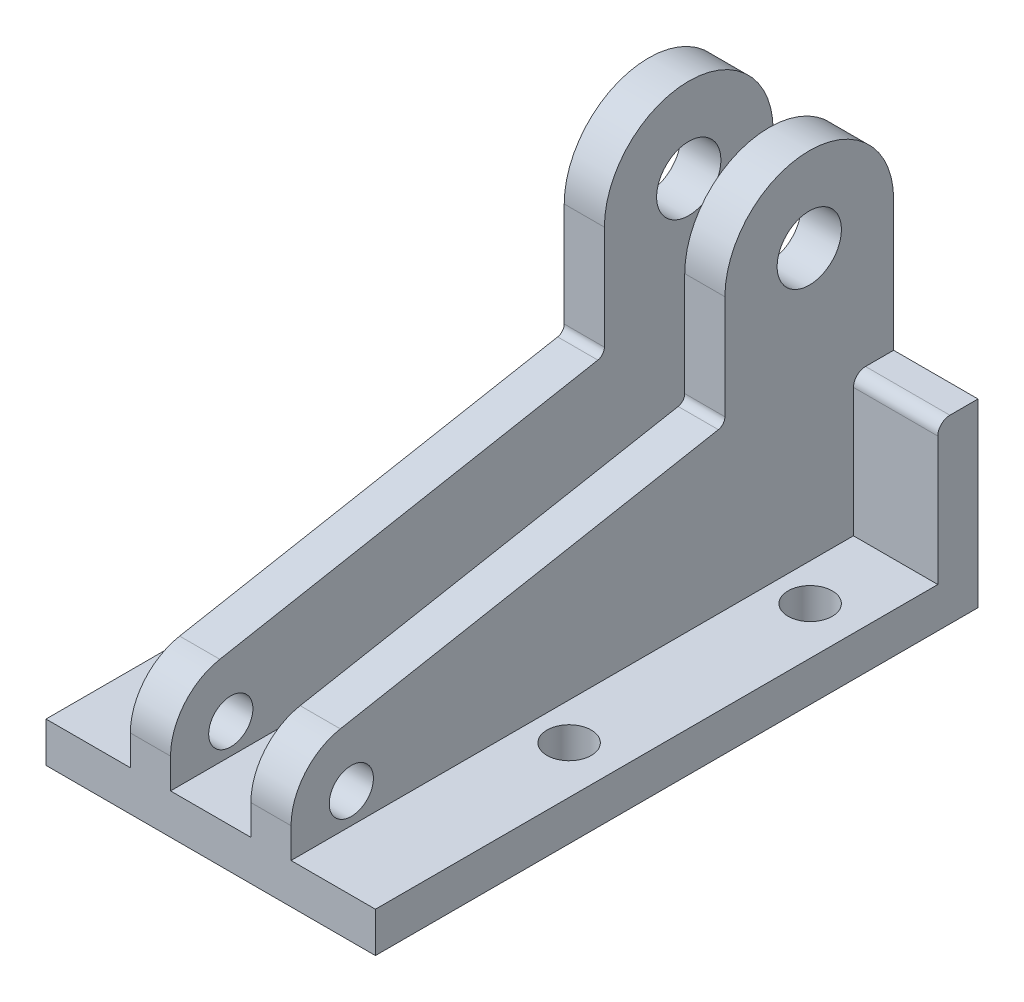
SolidWorks part; units mm, degrees
ref_plane "Front Plane" through (0, 0, 0) normal (0, 0, 1) x (1, 0, 0)
ref_plane "Top Plane" through (0, 0, 0) normal (0, 1, 0) x (1, 0, 0)
ref_plane "Right Plane" through (0, 0, 0) normal (1, 0, 0) x (0, 0, -1)
sketch "Sketch1" plane through (0, 0, 0) normal (1, 0, 0) x (0, 0, -1)
  line L0 (-84.2975, 0) -> (65.7025, 0)
  line L1 (65.7025, 0) -> (65.7025, 45)
  line L2 (-84.2975, 10) -> (55.7025, 10)
  line L3 (55.7025, 10) -> (55.7025, 42)
  line L4 (-84.2975, 0) -> (-84.2975, 10)
  line L5 (58.7025, 45) -> (65.7025, 45)
  line L6 (55.7025, 10) -> (55.7025, 45) construction
  arc A0 (58.7025, 45) -> (55.7025, 42) centre (58.7025, 42) ccw
  dimension "D4" = 3
  dimension "D1" = 150
  dimension "D2" = 45
  dimension "D3" = 10
extrude "Boss-Extrude1" add sketch "Sketch1" against normal blind 82
ref_plane "Plane1" through (-21, 0, 0) normal (1, 0, 0) x (0, 0, -1)
sketch "Sketch2" plane through (-21, 0, 0) normal (1, 0, 0) x (0, 0, -1)
  line L0 (65.7025, 45) -> (65.7025, 77.5314)
  line L1 (23.7025, 77.5314) -> (23.7025, 51.6632)
  line L2 (-84.2975, 10) -> (-84.2975, 17.5)
  line L3 (-72.0322, 32.2486) -> (22.0671, 49.6968)
  line L4 (55.7025, 10) -> (-84.2975, 10) construction
  line L5 (-84.2975, 10) -> (55.7025, 10)
  line L6 (55.7025, 10) -> (55.7025, 42)
  line L7 (65.7025, 45) -> (58.7025, 45)
  arc A0 (65.7025, 77.5314) -> (23.7025, 77.5314) centre (44.7025, 77.5314) ccw
  arc A1 (-72.0322, 32.2486) -> (-84.2975, 17.5) centre (-69.2975, 17.5) ccw
  arc A2 (55.7025, 42) -> (58.7025, 45) centre (58.7025, 42) cw
  circle A3 centre (44.7025, 77.5314) radius 8
  arc A4 (23.7025, 51.6632) -> (22.0671, 49.6968) centre (21.7025, 51.6632) cw
  circle A5 centre (-69.2975, 17.5) radius 5.5
  point P12 (-84.2975, 29.9743)
  point P25 (23.7025, 50)
  dimension "D1" = 21
  dimension "D3" = 15
  dimension "D5" = 2
  dimension "D2" = 7.5
  dimension "D4" = 40
extrude "Boss-Extrude2" add sketch "Sketch2" against normal blind 10
ref_plane "Plane2" through (-41, 0, 0) normal (1, 0, 0) x (0, 0, -1)
mirror "Mirror1" about plane through (-41, 0, 0) normal (1, 0, 0) of bodies 102
sketch "Sketch3" plane through (0, 10, 0) normal (0, 1, 0) x (1, 0, 0)
  line L0 (-21, 65.7025) -> (0, 65.7025) construction
  circle A0 centre (-11.7768, -24.2975) radius 5.5
  circle A1 centre (-11.7768, 35.7025) radius 5.5
  dimension "D1" = 30
  dimension "D2" = 60
extrude "Cut-Extrude1" cut sketch "Sketch3" against normal through all
